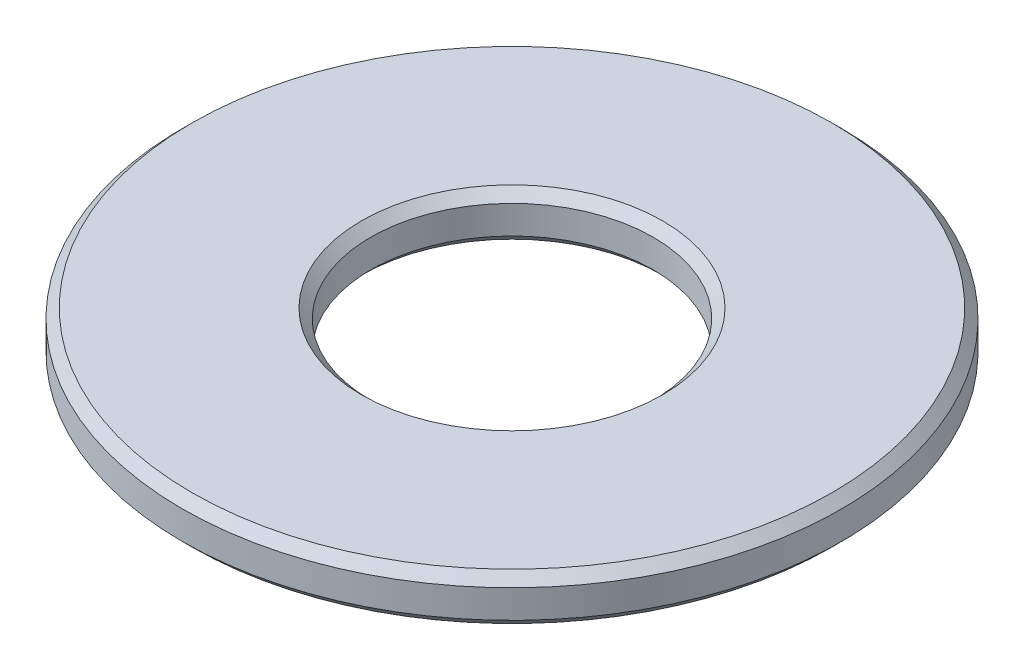
SolidWorks part; units mm, degrees
ref_plane "Front Plane" through (0, 0, 0) normal (0, 0, 1) x (1, 0, 0)
ref_plane "Top Plane" through (0, 0, 0) normal (0, 1, 0) x (1, 0, 0)
ref_plane "Right Plane" through (0, 0, 0) normal (1, 0, 0) x (0, 0, -1)
sketch "Sketch1" plane through (0, 0, 0) normal (0, 1, 0) x (1, 0, 0)
  circle A0 centre (0, 0) radius 3
  circle A1 centre (0, 0) radius 7
  dimension "D1" = 6
  dimension "D2" = 4
extrude "Boss-Extrude1" add sketch "Sketch1" along normal blind 1
chamfer "Chamfer1" distance 0.2 angle 45 4 edges at (0, 0, 3) (0, 0, 7) (0, 1, 3) (0, 1, 7)
